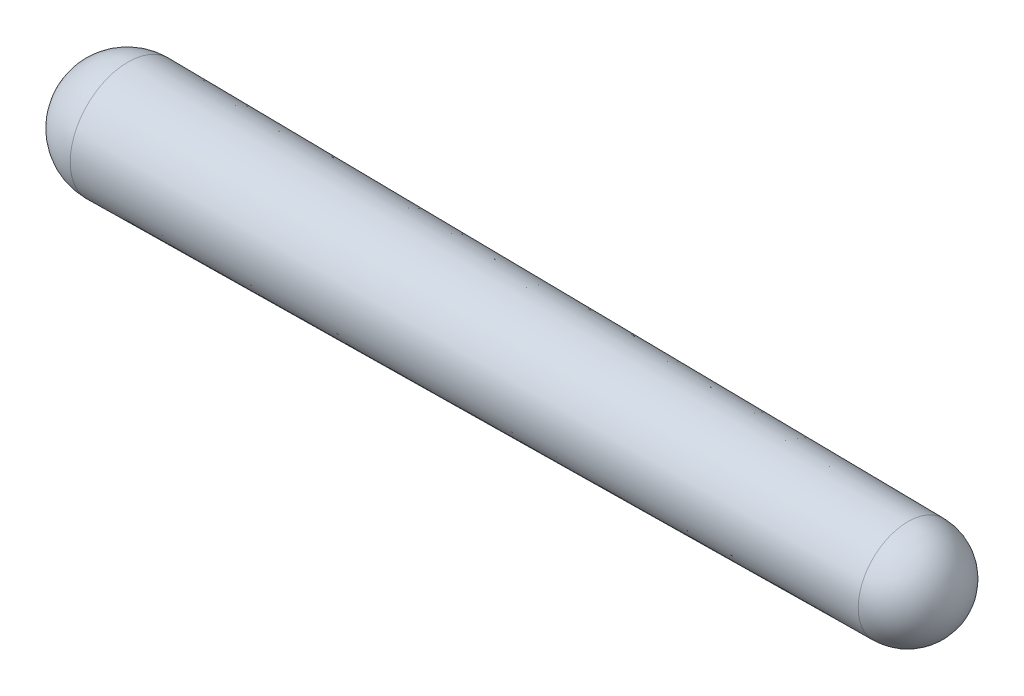
SolidWorks part; units mm, degrees
ref_plane "Front Plane" through (0, 0, 0) normal (0, 0, 1) x (1, 0, 0)
ref_plane "Top Plane" through (0, 0, 0) normal (0, 1, 0) x (1, 0, 0)
ref_plane "Right Plane" through (0, 0, 0) normal (1, 0, 0) x (0, 0, -1)
sketch "Sketch1" plane through (0, 0, 0) normal (0, 0, 1) x (1, 0, 0)
  line L0 (0, 0) -> (5458.1283, 0) construction
  line L1 (0, 0) -> (0, 5458.1283) construction
  line L2 (0.0325, 3.2498) -> (44.0281, 2.8099)
  line L4 (-3.25, 0) -> (46.81, 0)
  arc A0 (0.0325, 3.2498) -> (-3.25, 0) centre (0, 0) ccw
  arc A1 (46.81, 0) -> (44.0281, 2.8099) centre (44, 0) ccw
  point P11 (0, 0)
  point P12 (0, 0)
  dimension "D1" = 6.5
  dimension "D2" = 44
  dimension "D3" = 5.62
revolve "Revolve1" add sketch "Sketch1" angle 360 about L4
